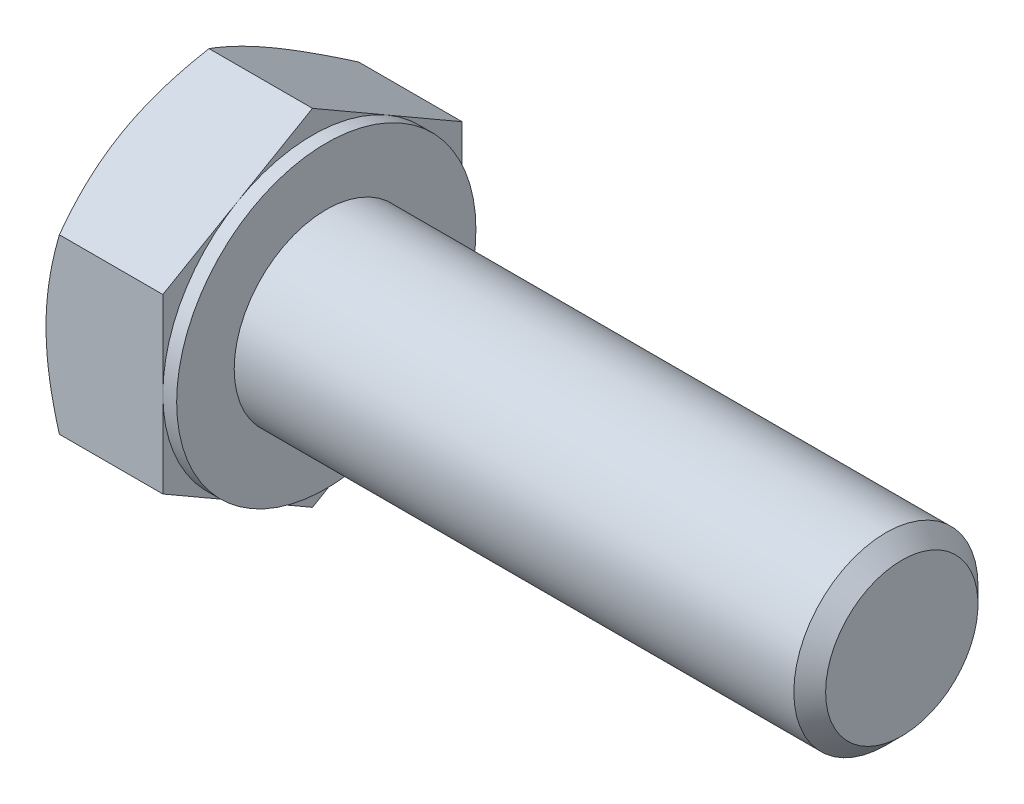
SolidWorks part; units mm, degrees
ref_plane "Plane1" through (0, 0, 0) normal (0, 0, 1) x (1, 0, 0)
ref_plane "Plane2" through (0, 0, 0) normal (0, 1, 0) x (1, 0, 0)
ref_plane "Plane3" through (0, 0, 0) normal (1, 0, 0) x (0, 0, -1)
sketch "Sketch1" plane through (0, 0, 0) normal (1, 0, 0) x (0, 0, -1)
  line L0 (6.5, 3.7528) -> (6.5, -3.7528)
  line L1 (-6.5, 3.7528) -> (-6.5, -3.7528)
  line L2 (6.5, -3.7528) -> (0, -7.5056)
  line L3 (0, -7.5056) -> (-6.5, -3.7528)
  line L4 (6.5, 3.7528) -> (0, 7.5056)
  line L5 (0, 7.5056) -> (-6.5, 3.7528)
  dimension "Width_flats" = 13
  dimension "D2" = 120
  dimension "D3" = 6.5
  dimension "D4" = 6.5
  dimension "D5" = 6.5
extrude "BaseHead" add sketch "Sketch1" along normal blind 5.675
sketch "BodySke" plane through (0, 0, 0) normal (0, 0, 1) x (1, 0, 0)
  line L0 (0, 3.7528) -> (0, -3.7528) construction
  line L1 (0, 0) -> (30.675, 0)
  line L2 (0, 0) -> (0, 4)
  line L3 (0, 4) -> (29.9845, 4)
  line L4 (30.675, 0) -> (30.675, 3.3095)
  line L5 (5.675, 7.5056) -> (5.675, 3.7528) construction
  line L6 (30.675, 3.3095) -> (29.9845, 4)
  line L7 (0, 0) -> (96.52, 0) construction
  line L8 (30.675, -3.3095) -> (29.9845, -4) construction
  line L9 (0, -4) -> (29.9845, -4) construction
  line L10 (6.925, 15.24) -> (6.925, -1.27) construction
  line L12 (5.675, 3.7528) -> (5.675, -3.7528) construction
  dimension "Length" = 25
  dimension "Body_ch_ang" = 45
  dimension "Diameter" = 8
  dimension "Minor_dia" = 6.619
  dimension "Advance" = 1.25
revolve "BaseBody" add sketch "BodySke"
cosmetic thread "ThreadCosmetic" [suppressed]
fillet "HeadFillet" [suppressed] radius 0.4
sketch "Sketch3" plane through (0, 0, 0) normal (0, 0, 1) x (1, 0, 0)
  line L0 (0, 6.5) -> (3.4673, 12.5056)
  line L1 (0, 7.5056) -> (0, 3.7528) construction
  line L2 (3.4673, 12.5056) -> (3.4673, 17.5056)
  line L3 (3.4673, 17.5056) -> (-10, 17.5056)
  line L4 (-10, 17.5056) -> (-10, 6.5)
  line L5 (-10, 6.5) -> (0, 6.5)
  line L6 (0, 0) -> (99.06, 0) construction
  line L7 (5.675, 7.5056) -> (0, 7.5056) construction
  dimension "D1" = 6.5
  dimension "D2" = 5
  dimension "D3" = 10
  dimension "D4" = 5
  dimension "Head_ch_ang" = 30
revolve "HeadChamfer" cut sketch "Sketch3" angle 360 about L6
sketch "Sketch4" plane through (0, 0, 0) normal (0, 0, 1) x (1, 0, 0)
  line L1 (5.675, 7.5056) -> (5.675, 3.7528) construction
  line L2 (5.675, 6.5) -> (5.075, 6.5)
  line L3 (5.675, 6.5) -> (5.675, 17.5056)
  line L4 (5.675, 17.5056) -> (5.075, 17.5056)
  line L5 (0, 0) -> (95.25, 0) construction
  line L6 (0, 0) -> (96.52, 0) construction
  line L7 (5.075, 6.5) -> (5.075, 17.5056)
  line L8 (5.675, 7.5056) -> (0.5806, 7.5056) construction
  dimension "D1" = 13
  dimension "D2" = 10
  dimension "Bearing_ht" = 0.6
revolve "BearingFace" cut sketch "Sketch4" angle 360 about L5
sketch "ThdSchSke" plane through (0, 0, 0) normal (0, 0, 1) x (1, 0, 0)
  line L0 (6.925, -3.3095) -> (6.4415, -4)
  line L1 (6.925, -3.3095) -> (7.4085, -4)
  line L2 (7.4085, -4) -> (7.4085, -5)
  line L3 (-3.175, 0) -> (5.1513, 0) construction
  line L5 (7.4085, -5) -> (6.4415, -5)
  line L6 (6.4415, -5) -> (6.4415, -4)
  dimension "Thread_minor" = 6.619
  dimension "Diameter" = 8
  dimension "Start" = 6.925
  dimension "SideAngle" = 55
  dimension "VeeAngle" = 70
  dimension "Overcut" = 10
revolve "ThreadSchematic" [suppressed] cut sketch "ThdSchSke" angle 360 about L3
pattern_linear "ThdSchPat" [suppressed]
equation "\"D3@Sketch1\" = \"Width_flats@Sketch1\" / 2"
equation "\"D4@Sketch1\" = \"D3@Sketch1\""
equation "\"D5@Sketch1\" = \"D4@Sketch1\""
equation "\"Thread_minor@ThreadCosmetic\" = \"Minor_dia@BodySke\""
equation "\"D1@Sketch3\" = \"Width_flats@Sketch1\" / 2"
equation "\"D1@Sketch4\" = \"Width_flats@Sketch1\""
equation "\"Thread_length@ThreadCosmetic\" = \"Length@BodySke\" - \"Advance@BodySke\""
equation "\"Thread_minor@ThdSchSke\" = \"Minor_dia@BodySke\""
equation "\"Diameter@ThdSchSke\" = \"Diameter@BodySke\""
equation "\"Overcut@ThdSchSke\" = \"Diameter@BodySke\" * 1.25"
equation "\"Start@ThdSchSke\" = \"Head_ht@BaseHead\" + \"Length@BodySke\" - \"Thread_length@ThreadCosmetic\"  '---Non-countersunk---"
equation "\"Num_threads@ThdSchPat\" = int( \"Thread_length@ThreadCosmetic\" / \"Advance@BodySke\" + 0.999 )  + 1"
equation "\"Advance@ThdSchPat\" = \"Thread_length@ThreadCosmetic\" /  (\"Num_threads@ThdSchPat\" - 1) 'relax it"
equation "\"Num_threads@ThdSchPat\" = \"Num_threads@ThdSchPat\" - sgn( \"Num_threads@ThdSchPat\" - 1) '---chamfered tips only---"
